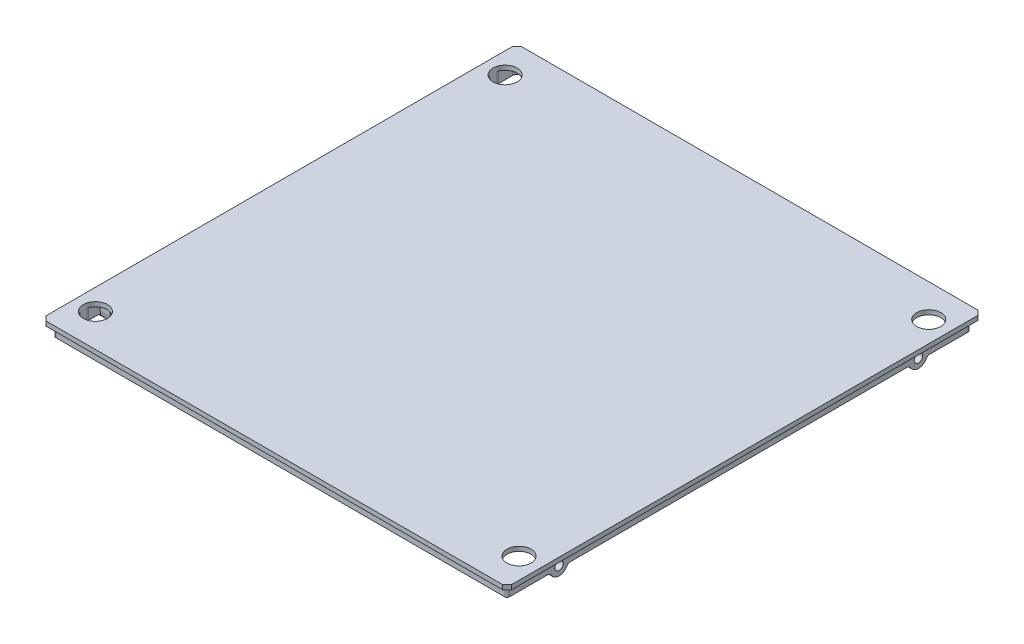
SolidWorks part; units mm, degrees
ref_plane "前视基准面" through (0, 0, 0) normal (0, 0, 1) x (1, 0, 0)
ref_plane "上视基准面" through (0, 0, 0) normal (0, 1, 0) x (1, 0, 0)
ref_plane "右视基准面" through (0, 0, 0) normal (1, 0, 0) x (0, 0, -1)
sketch "草图1" plane through (0, 0, 0) normal (0, 1, 0) x (1, 0, 0)
  line L1 (-52.2, 53.3) -> (52.2, 53.3)
  line L2 (-52.2, 53.3) -> (-52.2, -53.3)
  line L3 (-52.2, -53.3) -> (52.2, -53.3)
  line L4 (52.2, 53.3) -> (52.2, -53.3)
  line L5 (-52.2, 53.3) -> (52.2, -53.3) construction
  line L6 (-52.2, -53.3) -> (52.2, 53.3) construction
  point P0 (0, 0)
  dimension "D1" = 104.4
  dimension "D2" = 106.6
extrude "凸台-拉伸1" add sketch "草图1" along normal blind 1
sketch "草图2" plane through (0, 0, 0) normal (0, -1, 0) x (1, 0, 0)
  line L0 (50.85, -51.95) -> (50.85, 51.95)
  line L1 (50.85, 51.95) -> (-50.85, 51.95)
  line L2 (-50.85, 51.95) -> (-50.85, -51.95)
  line L3 (-50.85, -51.95) -> (50.85, -51.95)
  line L4 (52.2, -53.3) -> (52.2, 53.3)
  line L5 (52.2, 53.3) -> (-52.2, 53.3)
  line L6 (-52.2, 53.3) -> (-52.2, -53.3)
  line L7 (-52.2, -53.3) -> (52.2, -53.3)
  line L8 (52.2, -53.3) -> (52.2, 53.3) construction
  line L9 (52.2, 53.3) -> (-52.2, 53.3) construction
  line L10 (-52.2, 53.3) -> (-52.2, -53.3) construction
  line L11 (-52.2, -53.3) -> (52.2, -53.3) construction
  line L12 (50.05, -51.15) -> (50.05, 51.15)
  line L13 (50.05, 51.15) -> (-50.05, 51.15)
  line L14 (-50.05, 51.15) -> (-50.05, -51.15)
  line L15 (-50.05, -51.15) -> (50.05, -51.15)
  dimension "D1" = 0
  dimension "D2" = 1.35
  dimension "D3" = 0.8
extrude "凸台-拉伸2" add sketch "草图2" along normal blind 2.5
sketch "草图4" plane through (0, 1, 0) normal (0, 1, 0) x (1, 0, 0)
  circle A0 centre (47.5, 45.95) radius 1.7 construction
  circle A1 centre (-47.5, 45.95) radius 1.7 construction
  circle A2 centre (-47.5, -45.925) radius 1.7 construction
  circle A3 centre (47.5, -45.925) radius 1.7 construction
  circle A4 centre (47.5, 45.95) radius 1.7 construction
  circle A5 centre (-47.5, 45.95) radius 1.7 construction
  circle A6 centre (-47.5, -45.925) radius 1.7 construction
  circle A7 centre (47.5, -45.925) radius 1.7 construction
  circle A8 centre (47.5, 45.95) radius 2.7
  circle A9 centre (-47.5, 45.95) radius 2.7
  circle A10 centre (-47.5, -45.925) radius 2.7
  circle A11 centre (47.5, -45.925) radius 2.7
  dimension "D1" = 1
extrude "切除-拉伸1" cut sketch "草图4" against normal through all
sketch "草图5" plane through (0, 0, 0) normal (0, -1, 0) x (1, 0, 0)
  line L0 (50.05, 51.15) -> (-50.05, 51.15) construction
  line L1 (-0.4, 51.15) -> (0.4, 51.15)
  line L2 (-0.4, 51.15) -> (-0.4, -51.15)
  line L3 (-0.4, -51.15) -> (0.4, -51.15)
  line L4 (0.4, 51.15) -> (0.4, -51.15)
  line L6 (-50.05, -51.15) -> (50.05, -51.15) construction
  line L7 (50.05, -45.0626) -> (50.05, 45.0376) construction
  line L8 (-50.05, 0.4) -> (50.05, 0.4)
  line L9 (-50.05, 0.4) -> (-50.05, -0.4)
  line L10 (-50.05, -0.4) -> (50.05, -0.4)
  line L11 (50.05, 0.4) -> (50.05, -0.4)
  line L12 (-50.05, 0.4) -> (50.05, -0.4) construction
  line L13 (-50.05, -0.4) -> (50.05, 0.4) construction
  point P10 (0, -51.15)
  point P12 (0, 0)
  line M12 (-50.05, 45.0376) -> (-50.05, -45.0626)
  dimension "D1" = 0.8
  dimension "D2" = 0.8
extrude "凸台-拉伸3" add sketch "草图5" along normal up to surface (2.5 mm away) contours L10 L2 L8 M12 up to face at (0, -2.5, -0.0083)
fillet "圆角1" radius 1 24 edges at (-0.4, -1.25, 0.4) (-0.4, -1.25, 51.15) (-50.05, -1.25, 51.15) (-50.05, -1.25, 45.0376) (-50.05, -1.25, 46.8124) (-50.05, -1.25, 0.4) (50.05, -1.25, 46.8124) (50.05, -1.25, 45.0376) (50.05, -1.25, 51.15) (0.4, -1.25, 51.15) (0.4, -1.25, 0.4) (50.05, -1.25, 0.4) (0.4, -1.25, -51.15) (50.05, -1.25, -51.15) (50.05, -1.25, -45.0626) (50.05, -1.25, -46.8374) (50.05, -1.25, -0.4) (-50.05, -1.25, -46.8374) (-50.05, -1.25, -45.0626) (-50.05, -1.25, -51.15) (-0.4, -1.25, -51.15) (-0.4, -1.25, -0.4) (-50.05, -1.25, -0.4) (0.4, -1.25, -0.4)
fillet "圆角2" radius 0.5 4 edges at (-50.85, -1.25, -51.95) (-50.85, -1.25, 51.95) (50.85, -1.25, -51.95) (50.85, -1.25, 51.95)
chamfer "倒角1" distance 1 angle 45 4 edges at (52.2, 0.5, -53.3) (52.2, 0.5, 53.3) (-52.2, 0.5, 53.3) (-52.2, 0.5, -53.3)
sketch "草图6" plane through (50.85, 0, 0) normal (1, 0, 0) x (0, 0, -1)
  line L2 (-53.3, 0) -> (-53.3, 1) construction
  line L3 (-52.3, 1) -> (52.3, 1) construction
  line L4 (0, -2.5) -> (0, 13.1025) construction
  line L5 (51.45, -2.5) -> (-51.45, -2.5) construction
  circle A4 centre (-40.3, -2) radius 0.95
  circle A6 centre (-40.3, -2) radius 2
  circle A7 centre (40.3, -2) radius 2
  circle A8 centre (40.3, -2) radius 0.95
  dimension "D1" = 1.9
  dimension "D2" = 13
  dimension "D3" = 3
  dimension "D4" = 4
extrude "凸台-拉伸4" add sketch "草图6" against normal up to surface (0.8 mm away) up to face at (50.05, -1.25, 23.1411)
sketch "草图7" plane through (-50.85, 0, 0) normal (-1, 0, 0) x (0, 0, 1)
  circle A1 centre (-40.3, -2) radius 0.95
  circle A2 centre (-40.3, -2) radius 0.95
  circle A3 centre (-40.3, -2) radius 2
  circle A4 centre (-40.3, -2) radius 2
  circle A5 centre (40.3, -2) radius 2
  circle A6 centre (40.3, -2) radius 2
  circle A7 centre (40.3, -2) radius 0.95
  circle A8 centre (40.3, -2) radius 0.95
  dimension "D1" = 0
  dimension "D2" = 0
  dimension "D3" = 0
  dimension "D4" = 0
extrude "凸台-拉伸5" add sketch "草图7" against normal up to surface (0.8 mm away) up to face at (-50.05, -1.25, 23.1411)
sketch "草图8" plane through (50.85, 0, 0) normal (1, 0, 0) x (0, 0, -1)
  circle A1 centre (40.3, -2) radius 0.95
  circle A2 centre (40.3, -2) radius 0.95
  circle A7 centre (-40.3, -2) radius 0.95
  circle A8 centre (-40.3, -2) radius 0.95
  dimension "D1" = 0
  dimension "D4" = 0
extrude "切除-拉伸2" cut sketch "草图8" against normal up to surface (0.8 mm away) up to face at (50.05, -1.9167, 28.8607)
sketch "草图9" plane through (-50.85, 0, 0) normal (-1, 0, 0) x (0, 0, 1)
  circle A1 centre (40.3, -2) radius 0.95
  circle A2 centre (40.3, -2) radius 0.95
  circle A7 centre (-40.3, -2) radius 0.95
  circle A8 centre (-40.3, -2) radius 0.95
  dimension "D1" = 0
  dimension "D4" = 0
extrude "切除-拉伸3" cut sketch "草图9" against normal up to surface (0.8 mm away) up to face at (-50.05, -1.9167, -28.8691)
fillet "圆角3" radius 1 8 edges at (-50.45, -2.5, 42.2365) (-50.45, -2.5, 38.3635) (-50.45, -2.5, -38.3635) (-50.45, -2.5, -42.2365) (50.45, -2.5, -42.2365) (50.45, -2.5, -38.3635) (50.45, -2.5, 38.3635) (50.45, -2.5, 42.2365)
sketch "草图10" plane through (-50.85, 0, 0) normal (-1, 0, 0) x (0, 0, 1)
  line L0 (51.45, 0) -> (-51.45, 0) construction
  line L2 (-42.3, -2) -> (-42.3, 0)
  line L3 (-42.3, 0) -> (-38.3, 0)
  line L4 (-38.3, -2) -> (-38.3, 0)
  line L5 (0, 0) -> (0, 14.2096) construction
  line L6 (38.3, -2) -> (38.3, 0)
  line L7 (42.3, 0) -> (38.3, 0)
  line L8 (42.3, -2) -> (42.3, 0)
  circle A0 centre (40.3, -2) radius 0.95
  arc A1 (42.3, -2) -> (38.3, -2) centre (40.3, -2) cw
  circle A5 centre (-40.3, -2) radius 2
  arc A6 (-42.3, -2) -> (-38.3, -2) centre (-40.3, -2) ccw
  circle A7 centre (-40.3, -2) radius 0.95
  circle A8 centre (-40.3, -2) radius 0.95
  dimension "D3" = 0
  dimension "D4" = 0
extrude "凸台-拉伸6" add sketch "草图10" against normal blind 3
sketch "草图11" plane through (50.85, 0, 0) normal (1, 0, 0) x (0, 0, -1)
  line L3 (-38.3, -2) -> (-38.3, 0)
  line L4 (-38.3, 0) -> (-42.3, 0)
  line L5 (-42.3, 0) -> (-42.3, -2)
  line L6 (-38.3, -2) -> (-38.3, 0)
  line L7 (-38.3, 0) -> (-42.3, 0)
  line L8 (-42.3, 0) -> (-42.3, -2)
  line L9 (42.3, -2) -> (42.3, 0)
  line L10 (42.3, 0) -> (38.3, 0)
  line L11 (38.3, 0) -> (38.3, -2)
  line L12 (42.3, -2) -> (42.3, 0)
  line L13 (42.3, 0) -> (38.3, 0)
  line L14 (38.3, 0) -> (38.3, -2)
  circle A1 centre (40.3, -2) radius 0.95
  circle A2 centre (40.3, -2) radius 0.95
  circle A3 centre (-40.3, -2) radius 0.95
  circle A4 centre (-40.3, -2) radius 0.95
  arc A5 (-42.3, -2) -> (-38.3, -2) centre (-40.3, -2) ccw
  arc A6 (-42.3, -2) -> (-38.3, -2) centre (-40.3, -2) ccw
  arc A7 (38.3, -2) -> (42.3, -2) centre (40.3, -2) ccw
  arc A8 (38.3, -2) -> (42.3, -2) centre (40.3, -2) ccw
  dimension "D1" = 0
  dimension "D2" = 0
  dimension "D3" = 0
  dimension "D4" = 0
extrude "凸台-拉伸7" add sketch "草图11" against normal blind 3
